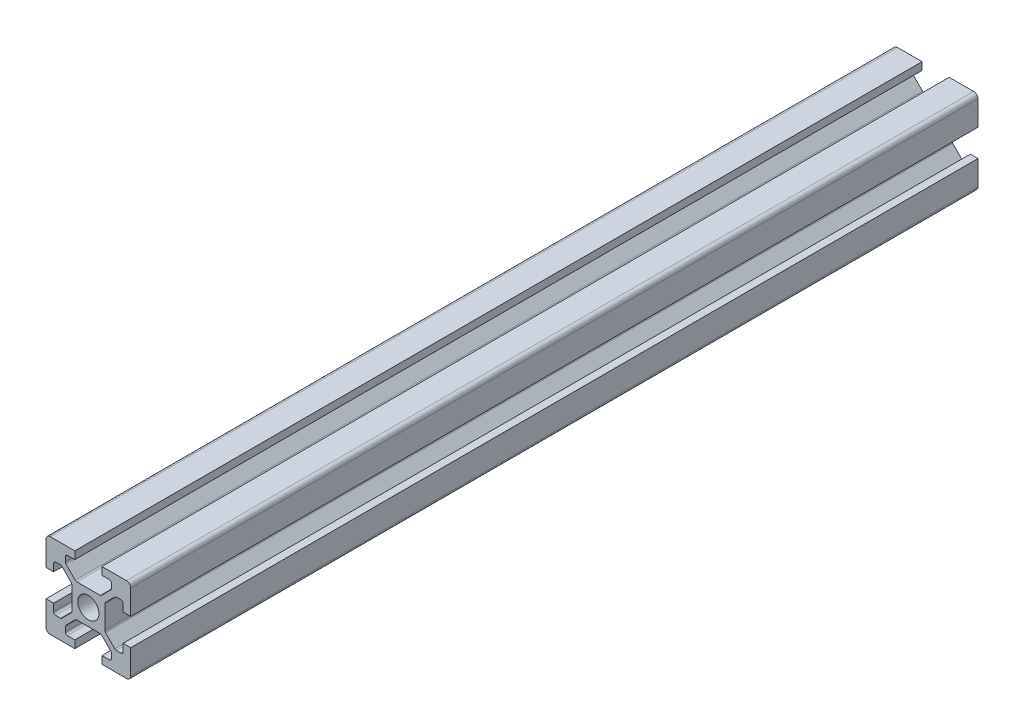
SolidWorks part; units mm, degrees
material "1060 Alloy"
ref_plane "Front Plane" through (0, 0, 0) normal (0, 0, 1) x (1, 0, 0)
ref_plane "Top Plane" through (0, 0, 0) normal (0, 1, 0) x (1, 0, 0)
ref_plane "Right Plane" through (0, 0, 0) normal (1, 0, 0) x (0, 0, -1)
sketch "Sketch1" plane through (0, 0, 0) normal (0, 0, 1) x (1, 0, 0)
  line L0 (20, 0) -> (-8.059, 28.059) construction
  line L1 (0, 0) -> (6.8, 0)
  line L2 (0, 0) -> (0, 6.8)
  line L3 (0, 20) -> (6.8, 20)
  line L4 (20, 0) -> (20, 6.8)
  line L5 (6.8, 20) -> (6.8, 18.2)
  line L6 (20, 20) -> (8.2322, 8.2322) construction
  line L7 (12.95, 6.1) -> (7.05, 6.1)
  line L8 (13.9, 7.05) -> (13.9, 12.95)
  line L9 (12.95, 13.9) -> (7.05, 13.9)
  line L10 (6.1, 7.05) -> (6.1, 12.95)
  line L11 (13.9, 6.1) -> (6.1, 13.9) construction
  line L12 (13.9, 13.9) -> (6.1, 6.1) construction
  line L13 (4.55, 16.4) -> (7.05, 13.9)
  line L14 (13.2, 18.2) -> (13.2, 20)
  line L15 (1.8, 6.8) -> (0, 6.8)
  line L16 (0, 13.2) -> (0, 20)
  line L17 (0, 13.2) -> (1.8, 13.2)
  line L18 (10, 10) -> (10, 13.9) construction
  line L19 (16.4, 4.55) -> (13.9, 7.05)
  line L20 (4.55, 16.4) -> (4.55, 18.2)
  line L21 (4.55, 18.2) -> (6.8, 18.2)
  line L22 (13.2, 18.2) -> (15.45, 18.2)
  line L23 (15.45, 18.2) -> (15.45, 16.4)
  line L24 (15.45, 16.4) -> (12.95, 13.9)
  line L25 (16.4, 4.55) -> (18.2, 4.55)
  line L26 (18.2, 4.55) -> (18.2, 6.8)
  line L27 (20, 6.8) -> (18.2, 6.8)
  line L28 (18.2, 13.2) -> (20, 13.2)
  line L29 (18.2, 13.2) -> (18.2, 15.45)
  line L30 (18.2, 15.45) -> (16.4, 15.45)
  line L31 (16.4, 15.45) -> (13.9, 12.95)
  line L32 (1.8, 4.55) -> (3.6, 4.55)
  line L33 (3.6, 15.45) -> (6.1, 12.95)
  line L34 (3.6, 15.45) -> (1.8, 15.45)
  line L35 (1.8, 15.45) -> (1.8, 13.2)
  line L36 (0, 13.2) -> (1.8, 13.2)
  line L37 (1.8, 6.8) -> (0, 6.8)
  line L38 (3.6, 4.55) -> (6.1, 7.05)
  line L39 (1.8, 6.8) -> (1.8, 4.55)
  line L40 (15.45, 3.6) -> (12.95, 6.1)
  line L41 (4.55, 3.6) -> (7.05, 6.1)
  line L42 (4.55, 1.8) -> (4.55, 3.6)
  line L43 (6.8, 1.8) -> (4.55, 1.8)
  line L44 (6.8, 1.8) -> (6.8, 0)
  line L45 (15.45, 3.6) -> (15.45, 1.8)
  line L46 (15.45, 1.8) -> (13.2, 1.8)
  line L47 (13.2, 0) -> (13.2, 1.8)
  line L48 (13.2, 20) -> (20, 20)
  line L49 (20, 13.2) -> (20, 20)
  line L50 (13.2, 0) -> (20, 0)
  line L51 (6.1, 6.1) -> (-5.5045, -5.5045) construction
  circle A0 centre (10, 10) radius 2.5
  point P25 (10, 16.4)
  point P39 (13.2, 19.1)
  point P46 (0.9, 6.8)
  dimension "D3" = 5
  dimension "D2" = 20
  dimension "D4" = 7.8
  dimension "D5" = 7.8
  dimension "D6" = 6.8
  dimension "D7" = 6.8
  dimension "D8" = 1.8
  dimension "D9" = 10.9
  dimension "D10" = 1.8
  dimension "D11" = 10.9
  dimension "D12" = 20
extrude "Boss-Extrude1" add sketch "Sketch1" along normal blind 200 contours L47 L50 L4 L27 L26 L25 L19 L8 L31 L30 L29 L28 L49 L48 L14 L22 L23 L24 L9 L13 L20 L21 L5 L3 L16 L17 L35 L34 L33 L10 L38 L32 L39 L15 L2 L1 L44 L43 L42 L41 L7 L40 L45 L46 A0
fillet "Fillet1" radius 1 4 edges at (20, 20, 100) (20, 0, 100) (0, 0, 100) (0, 20, 100)
fillet "Fillet2" radius 0.5 6 edges at (4.55, 18.2, 100) (4.55, 16.4, 100) (7.05, 13.9, 100) (15.45, 18.2, 100) (15.45, 16.4, 100) (12.95, 13.9, 100)
fillet "Fillet3" radius 0.5 6 edges at (18.2, 15.45, 100) (16.4, 15.45, 100) (13.9, 12.95, 100) (18.2, 4.55, 100) (13.9, 7.05, 100) (16.4, 4.55, 100)
fillet "Fillet4" radius 0.5 6 edges at (1.8, 15.45, 100) (3.6, 15.45, 100) (6.1, 12.95, 100) (3.6, 4.55, 100) (1.8, 4.55, 100) (6.1, 7.05, 100)
fillet "Fillet5" radius 0.5 6 edges at (7.05, 6.1, 100) (4.55, 3.6, 100) (4.55, 1.8, 100) (15.45, 1.8, 100) (15.45, 3.6, 100) (12.95, 6.1, 100)
